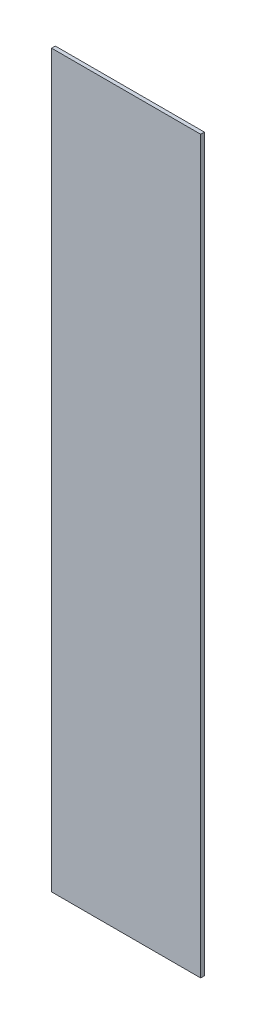
SolidWorks part; units mm, degrees
ref_plane "前视基准面" through (0, 0, 0) normal (0, 0, 1) x (1, 0, 0)
ref_plane "上视基准面" through (0, 0, 0) normal (0, 1, 0) x (1, 0, 0)
ref_plane "右视基准面" through (0, 0, 0) normal (1, 0, 0) x (0, 0, -1)
sketch "草图1" plane through (0, 0, 0) normal (0, 0, 1) x (1, 0, 0)
  line L1 (-10, -49) -> (10, -49)
  line L2 (-10, -49) -> (-10, 49)
  line L3 (-10, 49) -> (10, 49)
  line L4 (10, -49) -> (10, 49)
  line L5 (-10, -49) -> (10, 49) construction
  line L6 (-10, 49) -> (10, -49) construction
  point P0 (0, 0)
  dimension "D1" = 98
  dimension "D2" = 20
extrude "凸台-拉伸1" add sketch "草图1" along normal blind 0.5
